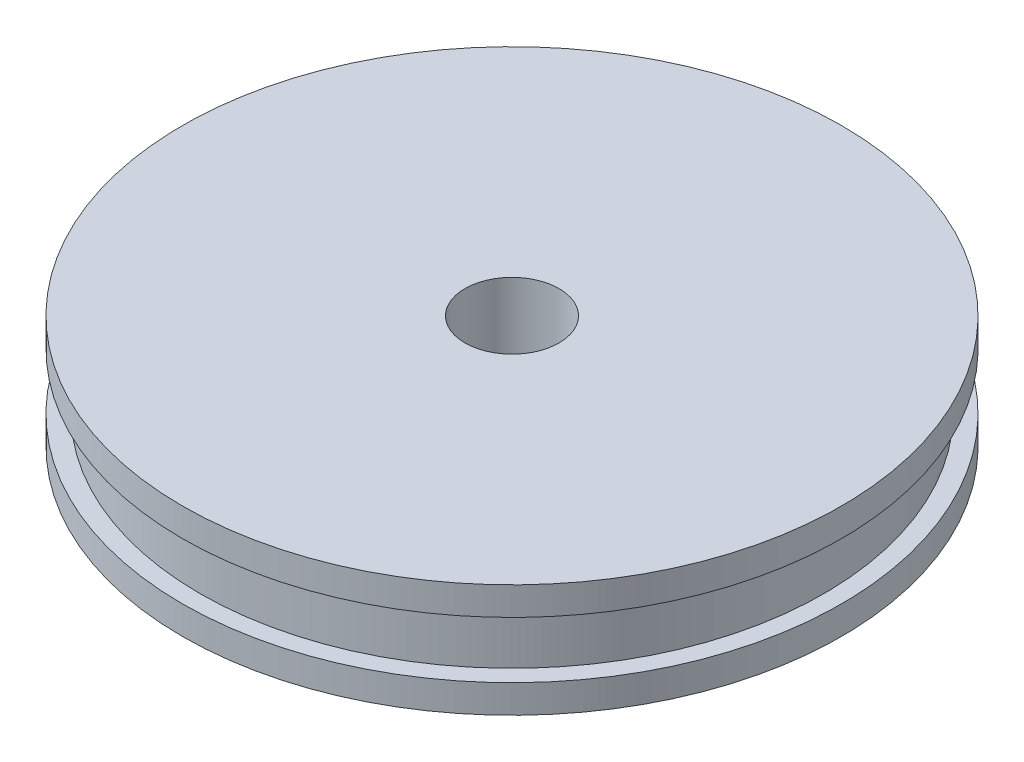
SolidWorks part; units mm, degrees
material "Alumina"
ref_plane "Front Plane" through (0, 0, 0) normal (0, 0, 1) x (1, 0, 0)
ref_plane "Top Plane" through (0, 0, 0) normal (0, 1, 0) x (1, 0, 0)
ref_plane "Right Plane" through (0, 0, 0) normal (1, 0, 0) x (0, 0, -1)
sketch "Sketch1" plane through (0, 0, 0) normal (0, 1, 0) x (1, 0, 0)
  circle A0 centre (0, 0) radius 5
  circle A1 centre (0, 0) radius 35
  dimension "D1" = 70
  dimension "D2" = 10
extrude "Boss-Extrude1" add sketch "Sketch1" along normal blind 12
sketch "Sketch2" plane through (0, 0, 0) normal (0, 0, 1) x (1, 0, 0)
  line L0 (-35, 12) -> (-35, 0) construction
  line L1 (-35, 9) -> (-33.1266, 9)
  line L2 (-35, 9) -> (-35, 3)
  line L3 (-35, 3) -> (-33.1266, 3)
  line L4 (-33.1266, 9) -> (-33.1266, 3)
  line L5 (35, 12) -> (-35, 12) construction
  line L6 (-35, 0) -> (35, 0) construction
  dimension "D1" = 3
  dimension "D2" = 3
sketch "Sketch3" plane through (0, 0, 0) normal (0, 0, 1) x (1, 0, 0)
  line L0 (0, 28.8851) -> (0, -13.5696) construction
revolve "Cut-Revolve1" cut sketch "Sketch2" angle 360 about L0
